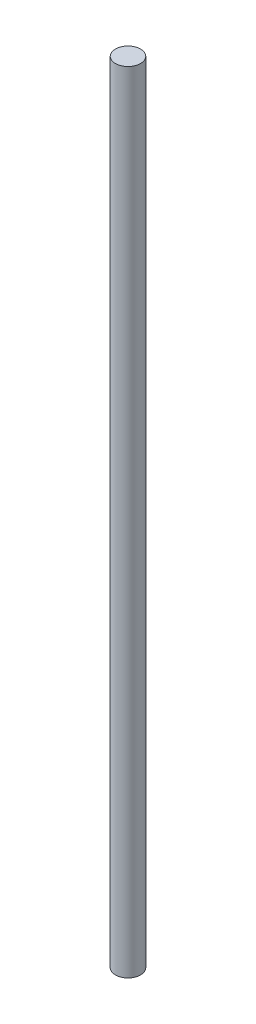
SolidWorks part; units mm, degrees
ref_plane "Спереди" through (0, 0, 0) normal (0, 0, 1) x (1, 0, 0)
ref_plane "Сверху" through (0, 0, 0) normal (0, 1, 0) x (1, 0, 0)
ref_plane "Справа" through (0, 0, 0) normal (1, 0, 0) x (0, 0, -1)
sketch "Эскиз1" plane through (0, 0, 0) normal (0, 1, 0) x (1, 0, 0)
  circle A0 centre (0, 0) radius 2.5
extrude "Вытянуть1" add sketch "Эскиз1" along normal blind 157
